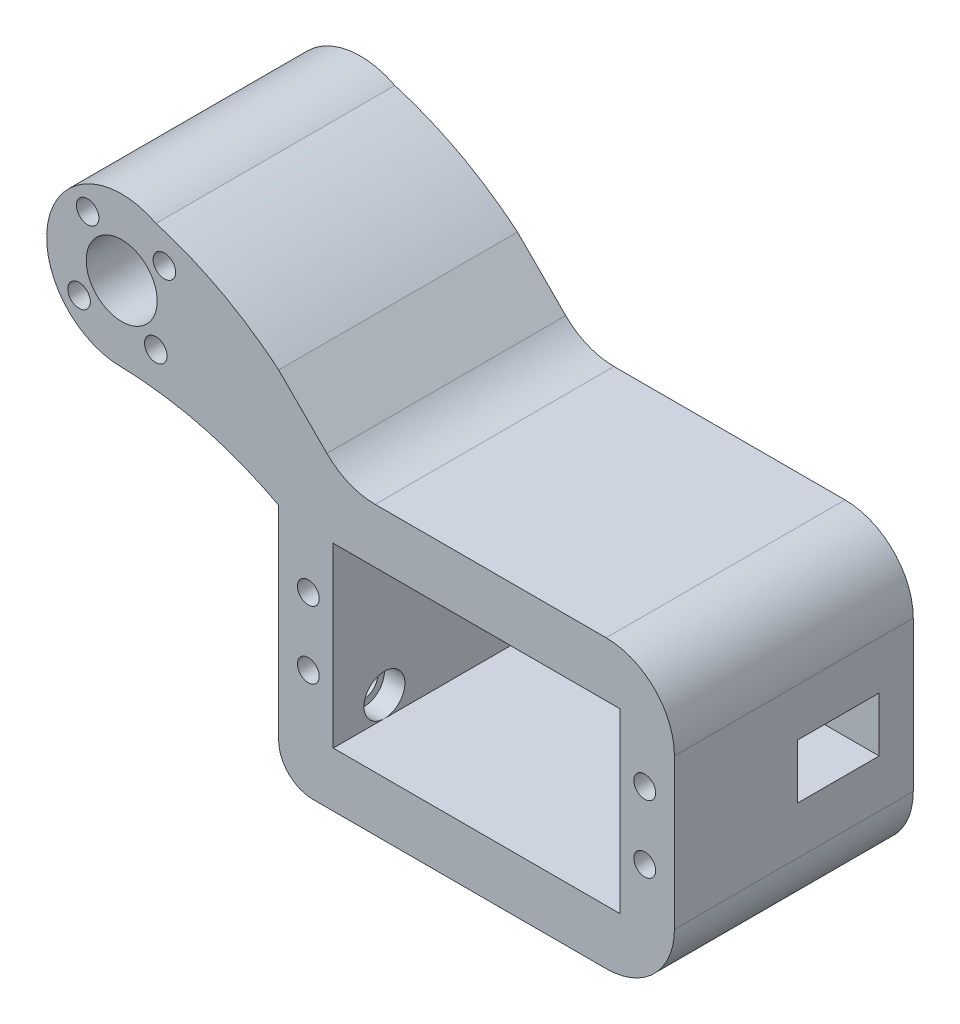
SolidWorks part; units mm, degrees
ref_plane "Front Plane" through (0, 0, 0) normal (0, 0, 1) x (1, 0, 0)
ref_plane "Top Plane" through (0, 0, 0) normal (0, 1, 0) x (1, 0, 0)
ref_plane "Right Plane" through (0, 0, 0) normal (1, 0, 0) x (0, 0, -1)
sketch "Sketch1" plane through (0, 0, 0) normal (0, 0, 1) x (1, 0, 0)
  line L0 (-29, 21) -> (29, 21)
  line L1 (-21, 13) -> (21, 13)
  line L2 (-21, 13) -> (-21, -13)
  line L3 (-21, -13) -> (21, -13)
  line L4 (21, 13) -> (21, -13)
  line L5 (-21, 13) -> (21, -13) construction
  line L6 (-21, -13) -> (21, 13) construction
  line L7 (29, 21) -> (29, -21)
  line L8 (-29, -21) -> (29, -21)
  line L9 (-29, 21) -> (-29, -21)
  point P0 (0, 0)
  dimension "D1" = 26
  dimension "D2" = 42
  dimension "D3" = 8
extrude "Boss-Extrude1" add sketch "Sketch1" along normal blind 30
sketch "Sketch2" plane through (0, 0, 0) normal (0, 0, -1) x (-1, 0, 0)
  line L1 (-29, 21) -> (29, 21)
  line L2 (-29, 21) -> (-29, -21)
  line L3 (-29, -21) -> (29, -21)
  line L4 (29, 21) -> (29, -21)
extrude "Boss-Extrude2" add sketch "Sketch2" along normal blind 5
sketch "Sketch3" plane through (-29, 0, 0) normal (-1, 0, 0) x (0, 0, 1)
  line L0 (30, 0) -> (-5, 0) construction
  line L1 (-5, -21) -> (10, -21)
  line L2 (-5, -21) -> (-5, -13)
  line L3 (-5, -13) -> (10, -13)
  line L4 (10, -21) -> (10, -13)
  line L5 (30, 21) -> (30, -21) construction
  line L6 (-5, -21) -> (-5, 21) construction
  line L7 (10, 21) -> (10, 13)
  line L8 (-5, 13) -> (10, 13)
  line L9 (-5, 21) -> (-5, 13)
  line L10 (-5, 21) -> (10, 21)
  dimension "D1" = 15
  dimension "D2" = 8
extrude "Cut-Extrude1" [suppressed] cut sketch "Sketch3" against normal through all
sketch "Sketch4" plane through (-29, 0, 0) normal (-1, 0, 0) x (0, 0, 1)
  circle A0 centre (22.5, 10) radius 1.75
  circle A1 centre (22.5, -10) radius 1.75
extrude "Cut-Extrude2" cut sketch "Sketch4" against normal up to surface (8 mm away) up to face at (-21, 0, 15)
sketch "Sketch5" plane through (-29, 0, 0) normal (-1, 0, 0) x (0, 0, 1)
  circle A0 centre (2.5, 10) radius 1.75
  circle A1 centre (2.5, -10) radius 1.75
extrude "Cut-Extrude3" cut sketch "Sketch5" against normal up to surface (8 mm away) up to face at (-21, 10, 20.75)
sketch "Sketch6" plane through (-29, 0, 0) normal (-1, 0, 0) x (0, 0, 1)
  circle A0 centre (22.5, 10) radius 2
  circle A1 centre (2.5, 10) radius 2
  circle A2 centre (2.5, -10) radius 2
  circle A3 centre (22.5, -10) radius 2
  dimension "D1" = 4
extrude "Cut-Extrude4" cut sketch "Sketch6" against normal up to surface (8 mm away) up to face at (-21, 10, 0.75)
sketch "Sketch7" plane through (21, 0, 0) normal (-1, 0, 0) x (0, 0, 1)
  circle A0 centre (22.5, 10) radius 3
  circle A1 centre (22.5, -10) radius 3
  circle A2 centre (2.5, 10) radius 3
  circle A3 centre (2.5, -10) radius 3
  dimension "D1" = 6
extrude "Cut-Extrude5" cut sketch "Sketch7" along normal blind 3 from surface at 42 starting at face at (-21, -10, 20.5)
sketch "Sketch8" plane through (0, 0, 30) normal (0, 0, 1) x (1, 0, 0)
  line L0 (-29, 13.8203) -> (-67.1295, 13.8203)
  line L1 (-29, 21) -> (-29, -21) construction
  line L2 (-67.1295, 13.8203) -> (-67.1295, 45.0077)
  line L3 (-67.1295, 45.0077) -> (-29, 45.0077)
  line L4 (-29, 45.0077) -> (-29, 13.8203)
extrude "Boss-Extrude3" add sketch "Sketch8" against normal up to surface (35 mm away) up to face at (0, 0, -5)
sketch "Sketch9" plane through (0, 0, 30) normal (0, 0, 1) x (1, 0, 0)
  circle A0 centre (-52, 30.8276) radius 5.2
  dimension "D1" = 10.4
extrude "Cut-Extrude6" cut sketch "Sketch9" against normal through all
sketch "Sketch10" plane through (0, 0, 30) normal (0, 0, 1) x (1, 0, 0)
  circle A0 centre (-45.7505, 35.8221) radius 1.65
  circle A1 centre (-47.0056, 24.5782) radius 1.65
  circle A2 centre (-56.9944, 37.0771) radius 1.65
  circle A3 centre (-58.2495, 25.8332) radius 1.65
  dimension "D1" = 3.3
extrude "Cut-Extrude7" cut sketch "Sketch10" against normal blind 15
fillet "Fillet1" radius 10 6 edges at (-67.1295, 45.0077, 12.5) (-29, 45.0077, 12.5) (29, -21, 12.5) (29, 21, 12.5) (-29, 21, 12.5) (-67.1295, 13.8203, 12.5)
sketch "Sketch11" plane through (0, 0, 30) normal (0, 0, 1) x (1, 0, 0)
  line L0 (-29, 31) -> (-29, 35.0077) construction
  line L1 (-57.1295, 13.8203) -> (-29, 13.8203) construction
  line L2 (-67.1295, 35.0077) -> (-67.1295, 23.8203) construction
  line L3 (-57.1295, 13.8203) -> (-29, 13.8203)
  line L4 (-67.1295, 35.0077) -> (-67.1295, 23.8203)
  line L5 (-29, 31) -> (-29, 35.0077)
  line L6 (-57.1295, 45.0077) -> (-39, 45.0077)
  arc A0 (-46.9636, 40.6069) -> (-52, 19.8276) centre (-52, 30.8276) ccw
  arc A1 (-67.1295, 23.8203) -> (-57.1295, 13.8203) centre (-57.1295, 23.8203) ccw construction
  arc A2 (-57.1295, 45.0077) -> (-67.1295, 35.0077) centre (-57.1295, 35.0077) ccw construction
  arc A3 (-29, 35.0077) -> (-39, 45.0077) centre (-39, 35.0077) ccw construction
  arc A4 (-67.1295, 23.8203) -> (-57.1295, 13.8203) centre (-57.1295, 23.8203) ccw
  arc A5 (-57.1295, 45.0077) -> (-67.1295, 35.0077) centre (-57.1295, 35.0077) ccw
  arc A6 (-29, 35.0077) -> (-39, 45.0077) centre (-39, 35.0077) ccw
  spline S0 degree 2 poles (-29, 31) (-36.9872, 37.6355) (-46.9636, 40.6069) knots 0 0 0 1 1 1
  spline S1 degree 2 poles (-52, 19.8276) (-39.6628, 19.4847) (-29, 13.8203) knots 0 0 0 1 1 1
  dimension "D1" = 22
extrude "Cut-Extrude8" cut sketch "Sketch11" against normal through all
sketch "Sketch12" plane through (0, 0, 30) normal (0, 0, 1) x (1, 0, 0)
  line L0 (-29, 31) -> (-19, 21)
  arc A0 (-29, 31) -> (-19, 21) centre (-19, 31) ccw construction
  arc A1 (-29, 31) -> (-19, 21) centre (-19, 31) ccw
extrude "Boss-Extrude4" add sketch "Sketch12" against normal up to surface (35 mm away)
fillet "Fillet2" radius 10 1 edges at (-19, 21, 12.5)
sketch "Sketch13" plane through (0, 0, 30) normal (0, 0, 1) x (1, 0, 0)
  circle A0 centre (24.65, 4.935) radius 1.6
  circle A1 centre (24.65, -4.935) radius 1.6
  circle A2 centre (-24.65, 4.935) radius 1.6
  circle A3 centre (-24.65, -4.935) radius 1.6
  dimension "D1" = 3.2
extrude "Cut-Extrude9" cut sketch "Sketch13" against normal blind 15
sketch "Sketch14" plane through (0, 0, -5) normal (0, 0, -1) x (-1, 0, 0)
  circle A0 centre (-10.25, 0) radius 6.6
  dimension "D1" = 13.2
extrude "Cut-Extrude10" cut sketch "Sketch14" against normal blind 5
sketch "Sketch15" plane through (21, 0, 0) normal (-1, 0, 0) x (0, 0, 1)
  line L0 (0, -13) -> (0, 13) construction
  line L1 (12, 4) -> (0, 4)
  line L2 (12, 4) -> (12, -4)
  line L3 (12, -4) -> (0, -4)
  line L4 (0, 4) -> (0, -4)
  line L5 (12, 4) -> (0, -4) construction
  line L6 (12, -4) -> (0, 4) construction
  point P0 (6, 0)
  point P7 (0, 0)
  dimension "D1" = 12
  dimension "D2" = 8
extrude "Cut-Extrude11" cut sketch "Sketch15" against normal through all
fillet "Fillet3" radius 5 1 edges at (-29, -21, 12.5)
